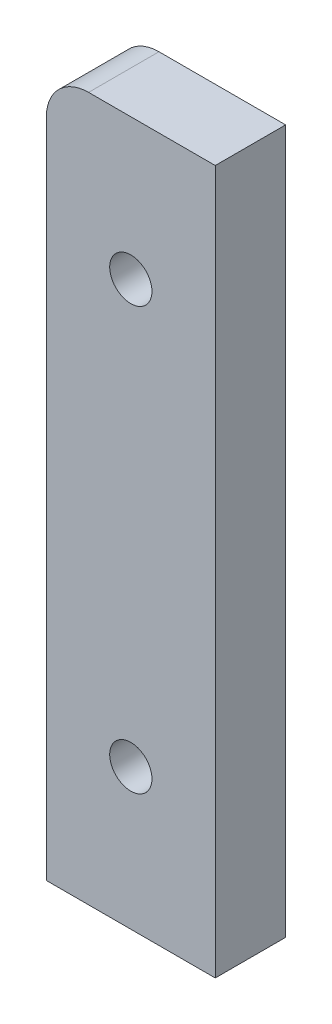
SolidWorks part; units mm, degrees
material "A-玻璃纤维"
ref_plane "前视基准面" through (0, 0, 0) normal (0, 0, 1) x (1, 0, 0)
ref_plane "上视基准面" through (0, 0, 0) normal (0, 1, 0) x (1, 0, 0)
ref_plane "右视基准面" through (0, 0, 0) normal (1, 0, 0) x (0, 0, -1)
sketch "草图1" plane through (0, 0, 0) normal (0, 0, 1) x (1, 0, 0)
  line L1 (-6, -25) -> (6, -25)
  line L2 (-6, -25) -> (-6, 25)
  line L3 (-6, 25) -> (6, 25)
  line L4 (6, -25) -> (6, 25)
  line L5 (-6, -25) -> (6, 25) construction
  line L6 (-6, 25) -> (6, -25) construction
  point P0 (0, 0)
  dimension "D1" = 50
  dimension "D2" = 12
extrude "凸台-拉伸1" add sketch "草图1" along normal blind 5
sketch "草图2" plane through (0, 0, 5) normal (0, 0, 1) x (1, 0, 0)
  line L0 (0, 0) -> (0, 15) construction
  circle A0 centre (0, 15) radius 1.5
  dimension "D1" = 3
  dimension "D2" = 15
extrude "切除-拉伸1" cut sketch "草图2" against normal through all
mirror "镜向1" about plane through (0, 0, 0) normal (0, 1, 0) of "切除-拉伸1"
fillet "圆角2" radius 3 1 edges at (-6, 25, 2.5)
